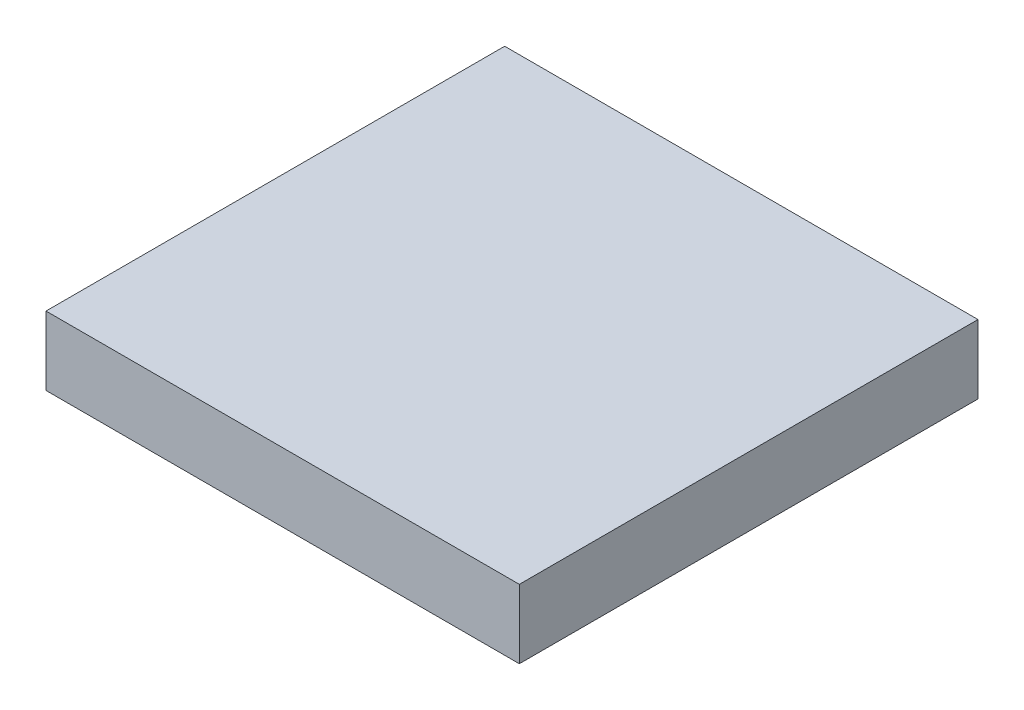
SolidWorks part; units mm, degrees
ref_plane "Front Plane" through (0, 0, 0) normal (0, 0, 1) x (1, 0, 0)
ref_plane "Top Plane" through (0, 0, 0) normal (0, 1, 0) x (1, 0, 0)
ref_plane "Right Plane" through (0, 0, 0) normal (1, 0, 0) x (0, 0, -1)
sketch "Sketch1" plane through (0, 0, 0) normal (0, 1, 0) x (1, 0, 0)
  line L1 (-103, -100) -> (103.4, -100)
  line L2 (-103, -100) -> (-103, 100)
  line L3 (-103, 100) -> (103.4, 100)
  line L4 (103.4, -100) -> (103.4, 100)
  dimension "D1" = 200
  dimension "D2" = 206.4
  dimension "D3" = 103
  dimension "D4" = 100
extrude "Boss-Extrude1" add sketch "Sketch1" along normal blind 30 contours L2 L3 L4 L1
